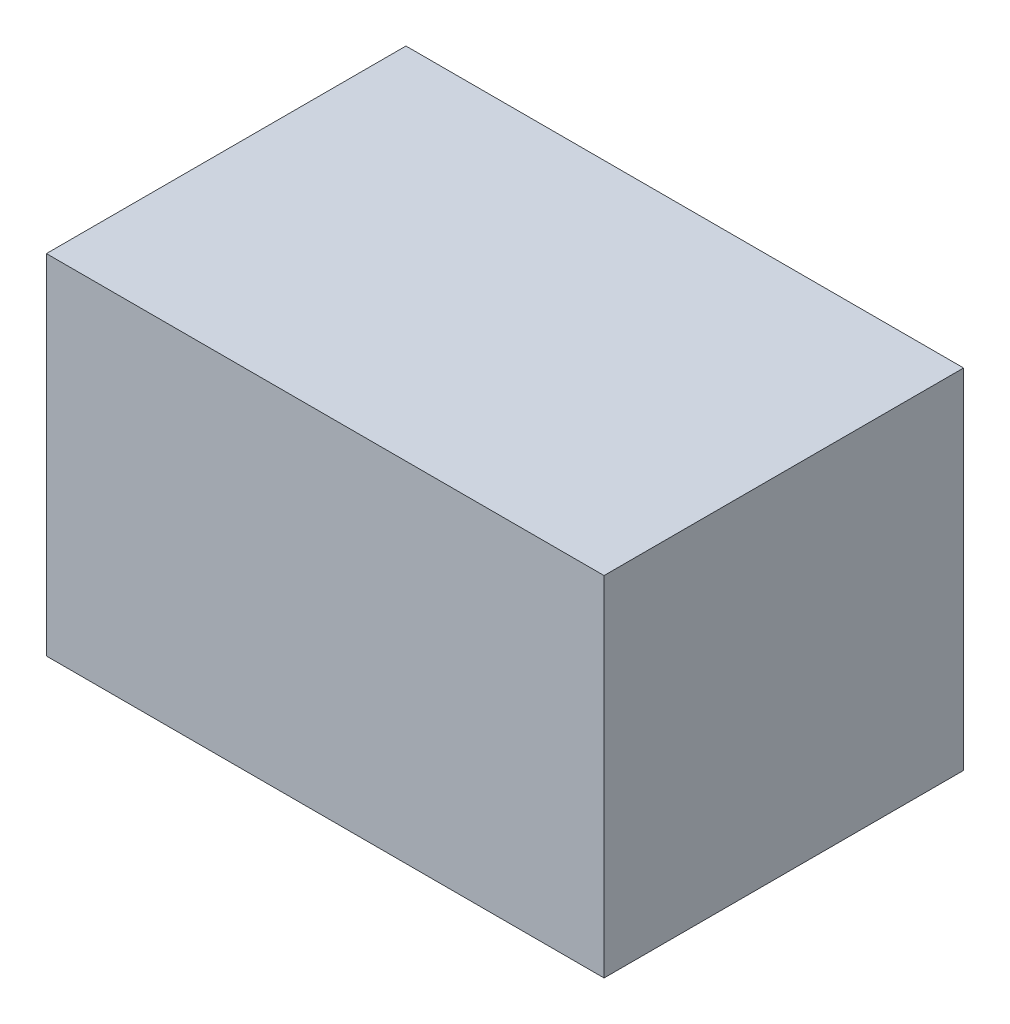
SolidWorks part; units mm, degrees
material "ABS"
ref_plane "Front Plane" through (0, 0, 0) normal (0, 0, 1) x (1, 0, 0)
ref_plane "Top Plane" through (0, 0, 0) normal (0, 1, 0) x (1, 0, 0)
ref_plane "Right Plane" through (0, 0, 0) normal (1, 0, 0) x (0, 0, -1)
sketch "Sketch1" plane through (0, 0, 0) normal (0, 1, 0) x (1, 0, 0)
  line L1 (0, 0) -> (152, 0)
  line L2 (0, 0) -> (0, 98)
  line L3 (0, 98) -> (152, 98)
  line L4 (152, 0) -> (152, 98)
  dimension "D1" = 152
  dimension "D2" = 98
extrude "Boss-Extrude1" add sketch "Sketch1" along normal blind 95
